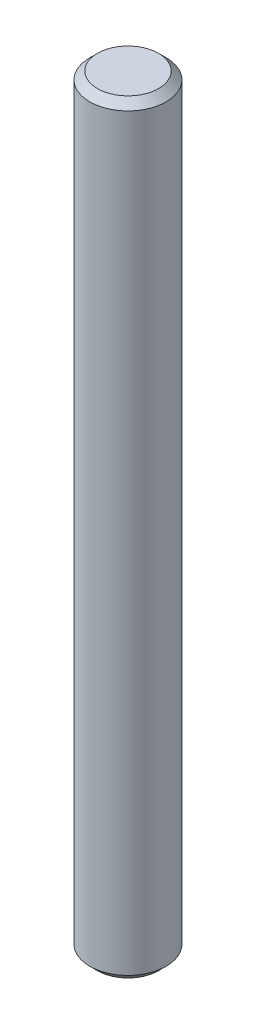
SolidWorks part; units mm, degrees
ref_plane "Front Plane" through (0, 0, 0) normal (0, 0, 1) x (1, 0, 0)
ref_plane "Top Plane" through (0, 0, 0) normal (0, 1, 0) x (1, 0, 0)
ref_plane "Right Plane" through (0, 0, 0) normal (1, 0, 0) x (0, 0, -1)
sketch "Sketch1" plane through (0, 0, 0) normal (0, 1, 0) x (1, 0, 0)
  circle A0 centre (0, 0) radius 2.5
  dimension "D1" = 5
extrude "Boss-Extrude1" add sketch "Sketch1" against normal blind 50
chamfer "Chamfer1" distance 0.5 angle 45 2 edges at (0, -50, 2.5) (0, 0, 2.5)
